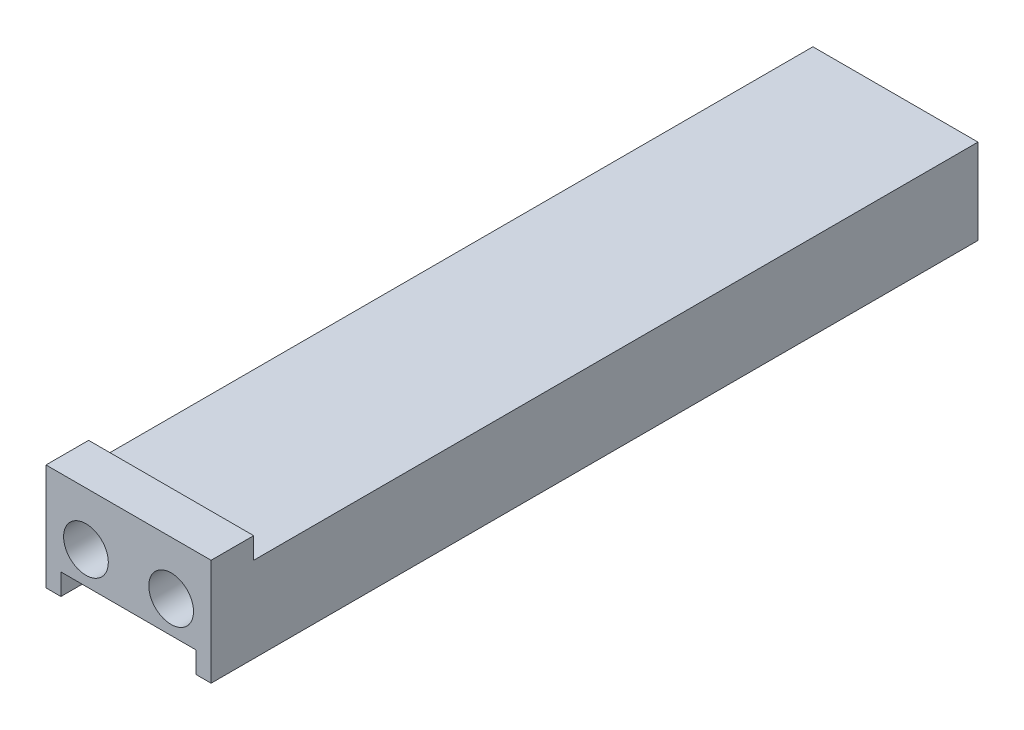
SolidWorks part; units mm, degrees
material "SKD11淬火HRC56-60"
ref_plane "前基準面" through (0, 0, 0) normal (0, 0, 1) x (1, 0, 0)
ref_plane "上基準面" through (0, 0, 0) normal (0, 1, 0) x (1, 0, 0)
ref_plane "右基準面" through (0, 0, 0) normal (1, 0, 0) x (0, 0, -1)
sketch "草图1" plane through (0, 0, 0) normal (0, 0, 1) x (1, 0, 0)
  line L1 (0, 0) -> (15.5, 0)
  line L2 (0, 0) -> (0, 8)
  line L3 (0, 8) -> (15.5, 8)
  line L4 (15.5, 0) -> (15.5, 8)
  dimension "D1" = 15.5
  dimension "D2" = 8
extrude "凸台-拉伸1" add sketch "草图1" along normal blind 72
sketch "草图2" plane through (0, 0, 0) normal (0, 0, -1) x (-1, 0, 0)
  line L0 (0, 0) -> (-15.5, 0) construction
  line L1 (-14.1, 0) -> (-1.4, 0)
  line L2 (-14.1, 0) -> (-14.1, 2)
  line L3 (-14.1, 2) -> (-1.4, 2)
  line L4 (-1.4, 0) -> (-1.4, 2)
  line L5 (-7.75, 0) -> (-7.75, 8) construction
  line L6 (-15.5, 8) -> (0, 8) construction
  line L7 (-15.5, 0) -> (-15.5, 8) construction
  dimension "D1" = 1.4
  dimension "D2" = 2
extrude "切除-拉伸1" cut sketch "草图2" against normal through all
sketch "草图3" plane through (0, 8, 0) normal (0, 1, 0) x (1, 0, 0)
  line L0 (15.5, -72) -> (15.5, 0) construction
  line L1 (0, -72) -> (15.5, -72)
  line L2 (0, -72) -> (0, -68)
  line L3 (0, -68) -> (15.5, -68)
  line L4 (15.5, -72) -> (15.5, -68)
  dimension "D1" = 4
extrude "凸台-拉伸2" add sketch "草图3" along normal blind 2
sketch "草图5" plane through (0, 0, 72) normal (0, 0, 1) x (1, 0, 0)
  line L0 (7.75, 2) -> (7.75, 10) construction
  line L1 (1.4, 2) -> (14.1, 2) construction
  line L2 (0, 10) -> (15.5, 10) construction
  circle A0 centre (3.75, 5) radius 2.1
  circle A1 centre (11.75, 5) radius 2.1
  dimension "D1" = 4.2
  dimension "D2" = 3
  dimension "D3" = 8
extrude "切除-拉伸3" cut sketch "草图5" against normal blind 10
